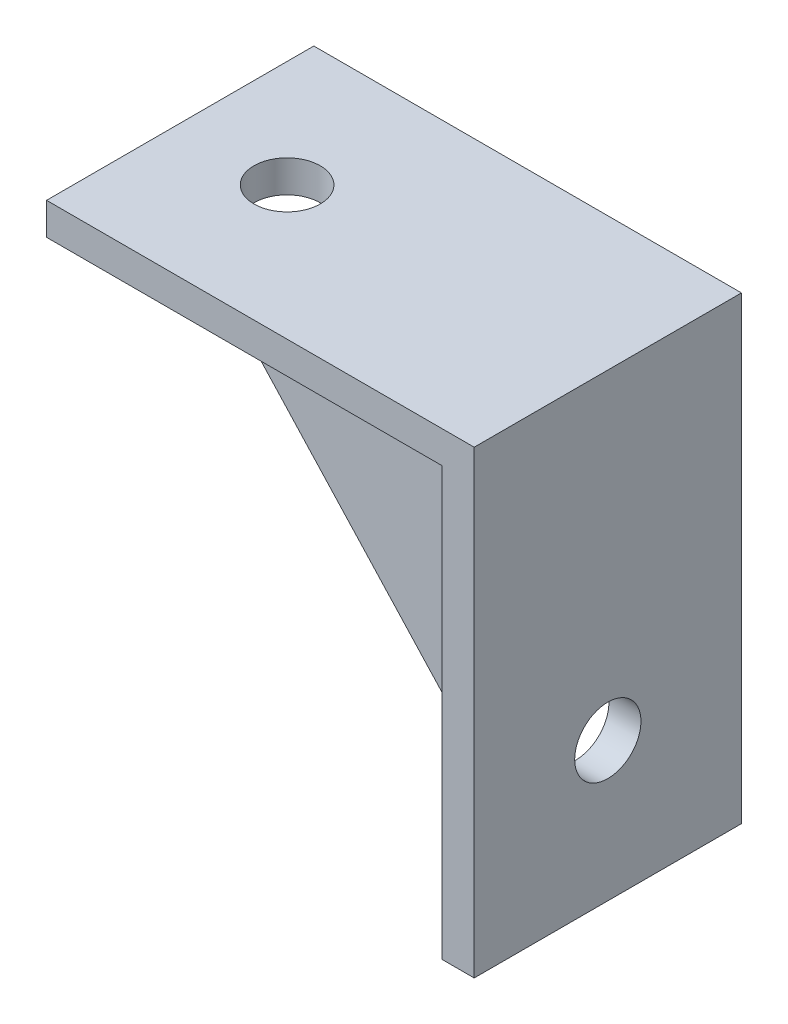
SolidWorks part; units mm, degrees
ref_plane "Front Plane" through (0, 0, 0) normal (0, 0, 1) x (1, 0, 0)
ref_plane "Top Plane" through (0, 0, 0) normal (0, 1, 0) x (1, 0, 0)
ref_plane "Right Plane" through (0, 0, 0) normal (1, 0, 0) x (0, 0, -1)
sketch "Sketch1" plane through (0, 0, 0) normal (0, 1, 0) x (1, 0, 0)
  line L0 (40, -12.5) -> (0, -12.5) construction
  line L1 (0, 0) -> (40, 0)
  line L2 (0, 0) -> (0, -25)
  line L3 (0, -25) -> (40, -25)
  line L4 (40, 0) -> (40, -25)
  circle A0 centre (10, -12.5) radius 3.1
  point P11 (0, 0)
  point P12 (0, 0)
  point P13 (0, 0)
  dimension "D3" = 6.2
  dimension "D1" = 25
  dimension "D2" = 40
  dimension "D4" = 10
extrude "Boss-Extrude1" add sketch "Sketch1" along normal blind 3
sketch "Sketch2" plane through (0, 0, 0) normal (0, -1, 0) x (1, 0, 0)
  line L0 (40, 0) -> (0, 0) construction
  line L1 (40, 25) -> (37, 25)
  line L2 (40, 25) -> (40, 0)
  line L3 (40, 0) -> (37, 0)
  line L4 (37, 25) -> (37, 0)
  dimension "D1" = 3
extrude "Boss-Extrude2" add sketch "Sketch2" along normal blind 40
sketch "Sketch3" plane through (37, 0, 0) normal (-1, 0, 0) x (0, 0, 1)
  line L0 (12.5, -40) -> (12.5, -0.9722) construction
  line L1 (25, -40) -> (0, -40) construction
  line L3 (0, 3) -> (25, 3) construction
  circle A1 centre (12.5, -27) radius 3.1
  dimension "D1" = 6.2
  dimension "D2" = 30
extrude "Cut-Extrude1" cut sketch "Sketch3" against normal through all
ref_plane "Plane1" through (0, 0, 12.5) normal (0, 0, 1) x (1, 0, 0)
sketch "Sketch4" plane through (0, 0, 12.5) normal (0, 0, 1) x (1, 0, 0)
  line L0 (15.2753, 0) -> (37, -23.5909)
  line L1 (0, 0) -> (37, 0) construction
  line L2 (37, -40) -> (37, 0) construction
  line L3 (37, -23.5909) -> (37, 0)
  line L5 (37, 0) -> (15.2753, 0)
  point P6 (0, 0)
  point P10 (0, 0)
extrude "Boss-Extrude3" add sketch "Sketch4" along normal mid plane 20
